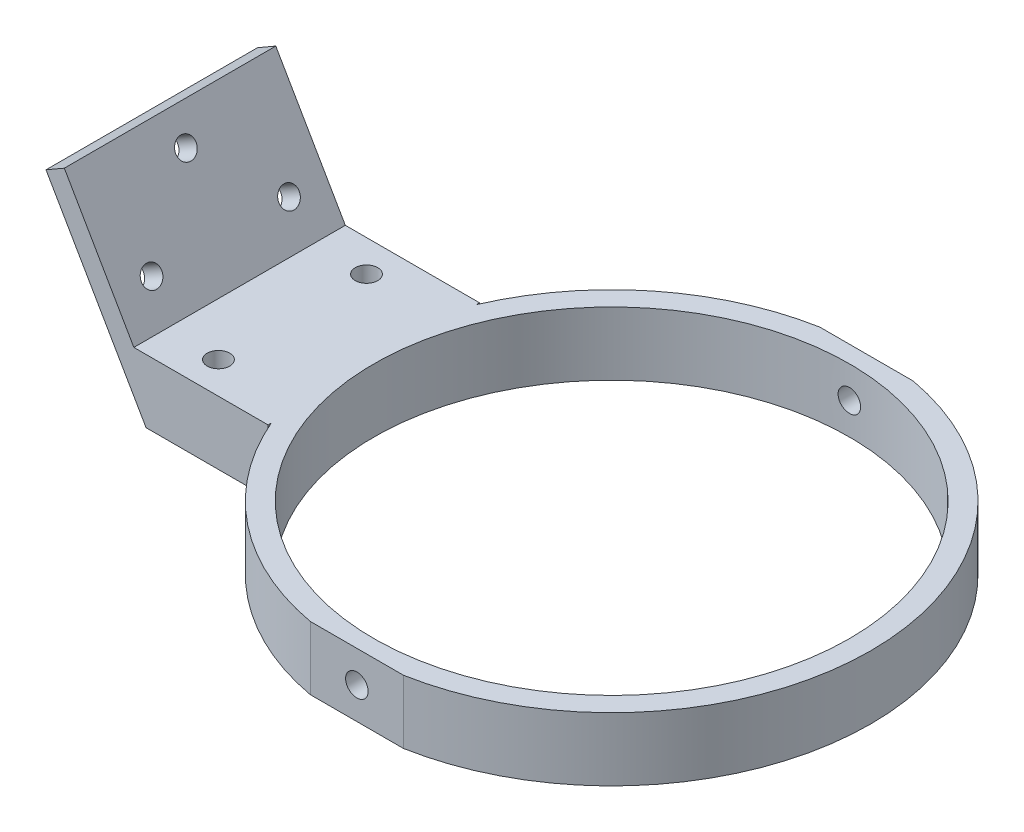
SolidWorks part; units mm, degrees
ref_plane "Front Plane" through (0, 0, 0) normal (0, 0, 1) x (1, 0, 0)
ref_plane "Top Plane" through (0, 0, 0) normal (0, 1, 0) x (1, 0, 0)
ref_plane "Right Plane" through (0, 0, 0) normal (1, 0, 0) x (0, 0, -1)
sketch "Sketch1" plane through (0, 0, 0) normal (0, 1, 0) x (1, 0, 0)
  circle A0 centre (0, 0) radius 29.845
  dimension "D1" = 59.69
extrude "Extrude-Thin1" add sketch "Sketch1" along normal blind 7.62 thin thin type two direction wall 1.27 second wall 1.27
sketch "Sketch2" plane through (0, 7.62, 0) normal (0, 1, 0) x (1, 0, 0)
  line L0 (-28.575, 0) -> (-28.575, -12.7)
  line L1 (-28.575, -12.7) -> (-47.625, -12.7)
  line L2 (-47.625, 12.7) -> (-47.625, -12.7)
  line L6 (-28.575, 0) -> (-28.575, 12.7)
  line L7 (-28.575, 12.7) -> (-47.625, 12.7)
  circle A1 centre (0, 0) radius 28.575 construction
  dimension "D1" = 12.7
  dimension "D2" = 12.7
  dimension "D3" = 19.05
extrude "Boss-Extrude1" add sketch "Sketch2" against normal blind 7.62 contours L7 L2 L1 L0 L6
sketch "Sketch3" plane through (0, 0, 12.7) normal (0, 0, 1) x (1, 0, 0)
  line L0 (-47.625, 0) -> (-43.2256, 0)
  line L1 (-28.575, 0) -> (-47.625, 0) construction
  line L2 (-43.2256, 0) -> (-47.625, 7.62)
  line L3 (-47.625, 7.62) -> (-47.625, 0)
  dimension "D1" = 30
extrude "Cut-Extrude1" cut sketch "Sketch3" against normal up to next and the other way through all
sketch "Sketch4" plane through (-32.4192, -18.7172, 0) normal (-0.866, -0.5, 0) x (0, 0, 1)
  line L1 (-12.7, 30.4116) -> (12.7, 30.4116) construction
  line L4 (-12.7, 21.6128) -> (12.7, 21.6128)
  line L6 (-12.7, 21.6128) -> (-12.7, 45.6516)
  line L7 (-12.7, 45.6516) -> (12.7, 45.6516)
  line L8 (12.7, 21.6128) -> (12.7, 45.6516)
  dimension "D1" = 15.24
  dimension "D2" = 25.4
extrude "Boss-Extrude2" add sketch "Sketch4" against normal blind 2.54 contours L6 L7 L8 L4
hole_wizard "#2 Clearance Hole1" positions "Sketch6" profile "Sketch5" hole size "#2" standard "ANSI Inch" end condition through all
sketch "Sketch6" plane through (-30.2195, -17.4472, 0) normal (0.866, 0.5, 0) x (0, 0, -1)
  line L0 (12.7, 28.9451) -> (12.7, 45.6516) construction
  line L3 (12.7, 45.6516) -> (-12.7, 45.6516) construction
  line L4 (-12.7, 28.9451) -> (-12.7, 45.6516) construction
  point P0 (-8.255, 33.5866)
  point P2 (8.255, 33.5866)
  point P21 (0, 41.8416)
  dimension "D1" = 16.51
  dimension "D2" = 4.445
  dimension "D3" = 12.065
  dimension "D6" = 12.065
  dimension "D7" = 3.81
  dimension "D8" = 12.7
sketch "Sketch5" plane through (-47.0128, 11.6396, 8.255) normal (0, 0, 1) x (-0.5, 0.866, 0)
  line L0 (0, 0) -> (0, 12.9491)
  line L1 (0, 12.9491) -> (1.2192, 12.9491)
  line L2 (1.2192, 12.9491) -> (1.2192, 0)
  line L5 (1.2192, 0) -> (0, 0)
  line L11 (0, -6.35) -> (0, 107.95) construction
  dimension "Thru Hole Dia." = 2.4384
  dimension "Thru Hole Depth" = 12.9491
hole_wizard "#6-32 Tapped Hole1" positions "Sketch8" profile "Sketch7" tap size "#6-32" standard "ANSI Inch" end condition through all
sketch "Sketch8" plane through (0, 7.62, 0) normal (0, 1, 0) x (1, 0, 0)
  line L0 (-44.6921, 12.7) -> (-44.6921, -12.7) construction
  line L1 (-28.575, 12.7) -> (-44.6921, 12.7) construction
  line L4 (-28.575, -12.7) -> (-44.6921, -12.7) construction
  point P0 (-38.3421, -8.89)
  point P2 (-38.3421, 8.89)
  dimension "D1" = 6.35
  dimension "D2" = 6.35
  dimension "D3" = 3.81
  dimension "D4" = 3.81
sketch "Sketch7" plane through (-38.3421, 7.62, 8.89) normal (1, 0, 0) x (0, 0, 1)
  line L0 (0, 0) -> (0, 7.62)
  line L1 (0, 7.62) -> (1.3525, 7.62)
  line L2 (1.3525, 7.62) -> (1.3525, 0)
  line L5 (1.3525, 0) -> (0, 0)
  line L11 (0, -6.35) -> (0, 107.95) construction
  dimension "Thru Tap Drill Dia." = 2.7051
  dimension "Thru Tap Drill Depth" = 7.62
cosmetic thread "Hole Thread1" parameters "D2"=3.5052
cosmetic thread "Hole Thread2" parameters "D2"=3.5052
sketch "Sketch9" plane through (0, 7.62, 0) normal (0, 1, 0) x (1, 0, 0)
  line L0 (-10.16, 30.607) -> (10.16, 30.607)
  line L4 (10.16, 31.115) -> (10.16, 30.607)
  line L5 (-10.16, 30.607) -> (-10.16, 31.115)
  line L6 (-10.16, 31.115) -> (10.16, 31.115)
  dimension "D1" = 20.32
  dimension "D3" = 0.508
extrude "Cut-Extrude2" cut sketch "Sketch9" against normal through all
sketch "Sketch10" plane through (0, 7.62, 0) normal (0, 1, 0) x (1, 0, 0)
  line L0 (0, -31.115) -> (14.7426, -31.115)
  line L1 (14.7426, -31.115) -> (14.7426, -30.607)
  line L2 (14.7426, -30.607) -> (-16.08, -30.607)
  line L3 (-16.08, -30.607) -> (-16.08, -31.115)
  line L4 (-16.08, -31.115) -> (0, -31.115)
  arc A0 (-28.575, -12.3131) -> (5.5995, 30.607) centre (0, 0) ccw construction
  dimension "D1" = 0.508
extrude "Cut-Extrude3" cut sketch "Sketch10" against normal through all
hole_wizard "#6-32 Tapped Hole2" positions "Sketch12" profile "Sketch11" tap size "#6-32" standard "ANSI Inch"
sketch "Sketch12" plane through (0, 0, -30.607) normal (0, 0, -1) x (-1, 0, 0)
  line L0 (5.5995, 7.62) -> (-5.5995, 7.62) construction
  point P0 (0, 3.81)
  dimension "D1" = 3.81
sketch "Sketch11" plane through (0, 3.81, -30.607) normal (1, 0, 0) x (0, 1, 0)
  line L0 (0, 0) -> (0, 11.9887)
  line L1 (0, 11.9887) -> (1.3525, 11.176)
  line L2 (1.3525, 11.176) -> (1.3525, 0)
  line L5 (1.3525, 0) -> (0, 0)
  line L10 (0, 11.9887) -> (-1.3525, 11.176) construction
  line L11 (0, -6.35) -> (0, 107.95) construction
  dimension "Tap Drill Dia." = 2.7051
  dimension "Tap Drill Depth" = 11.176
  dimension "Drill Angle" = 118
cosmetic thread "Hole Thread3" parameters "D1"=2.064, "D2"=3.5052
hole_wizard "#6-32 Tapped Hole3" positions "Sketch14" profile "Sketch13" tap size "#6-32" standard "ANSI Inch"
sketch "Sketch14" plane through (0, 0, 30.607) normal (0, 0, 1) x (1, 0, 0)
  line L0 (5.5995, 7.62) -> (-5.5995, 7.62) construction
  point P8 (0, 3.81)
  dimension "D1" = 3.81
sketch "Sketch13" plane through (0, 3.81, 30.607) normal (1, 0, 0) x (0, -1, 0)
  line L0 (0, 0) -> (0, 11.9887)
  line L1 (0, 11.9887) -> (1.3525, 11.176)
  line L2 (1.3525, 11.176) -> (1.3525, 0)
  line L5 (1.3525, 0) -> (0, 0)
  line L10 (0, 11.9887) -> (-1.3525, 11.176) construction
  line L11 (0, -6.35) -> (0, 107.95) construction
  dimension "Tap Drill Dia." = 2.7051
  dimension "Tap Drill Depth" = 11.176
  dimension "Drill Angle" = 118
cosmetic thread "Hole Thread4" parameters "D1"=2.064, "D2"=3.5052
